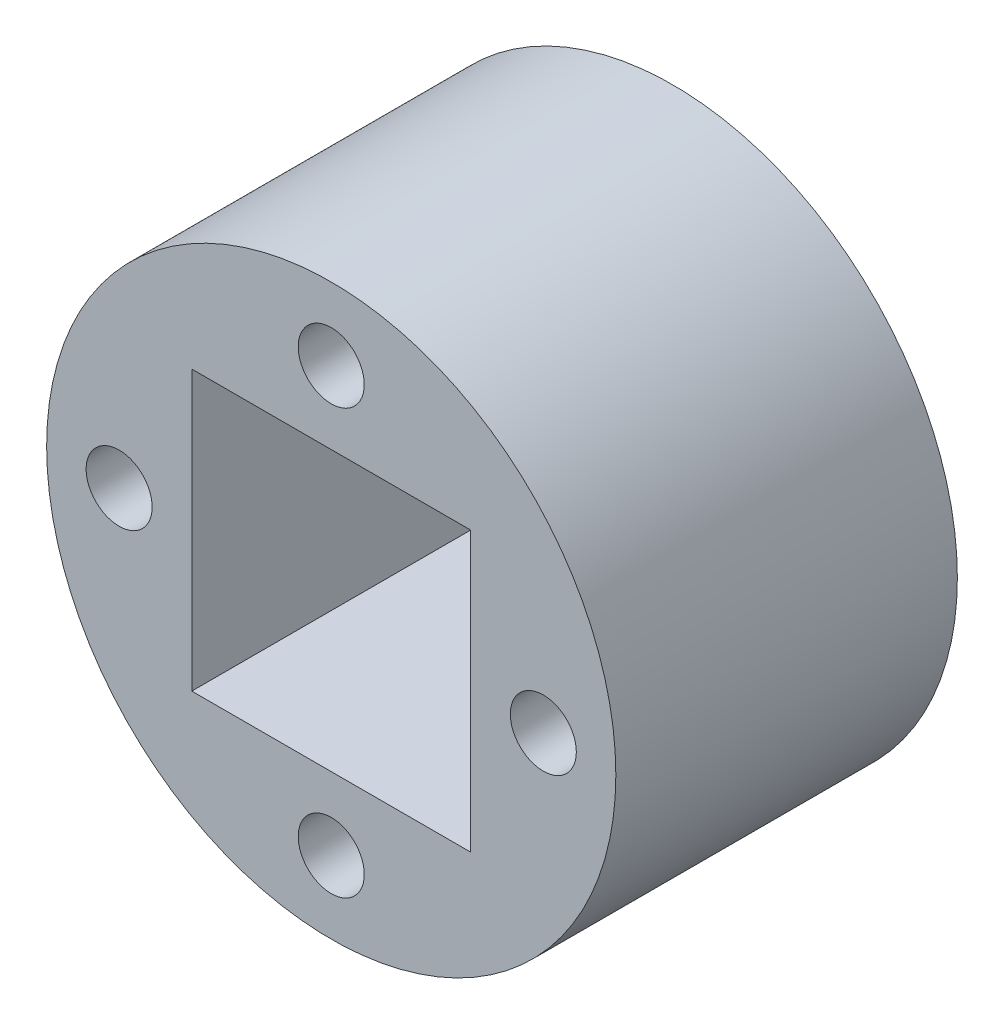
SolidWorks part; units mm, degrees
ref_plane "Front Plane" through (0, 0, 0) normal (0, 0, 1) x (1, 0, 0)
ref_plane "Top Plane" through (0, 0, 0) normal (0, 1, 0) x (1, 0, 0)
ref_plane "Right Plane" through (0, 0, 0) normal (1, 0, 0) x (0, 0, -1)
sketch "Sketch1" plane through (0, 0, 0) normal (0, 0, 1) x (1, 0, 0)
  circle A0 centre (0, 0) radius 12.5
  dimension "D2" = 25
extrude "Boss-Extrude1" add sketch "Sketch1" along normal mid plane 15
sketch "Sketch10" plane through (0, 0, 7.5) normal (0, 0, 1) x (1, 0, 0)
  circle A0 centre (0, 0) radius 12.5
  dimension "D1" = 25
sketch "Sketch8" plane through (0, 0, 7.5) normal (0, 0, 1) x (1, 0, 0)
  line L2 (-6.125, 6.125) -> (6.125, 6.125)
  line L3 (-6.125, 6.125) -> (-6.125, -6.125)
  line L4 (-6.125, -6.125) -> (6.125, -6.125)
  line L5 (6.125, 6.125) -> (6.125, -6.125)
  line L6 (-6.125, 6.125) -> (6.125, -6.125) construction
  line L7 (-6.125, -6.125) -> (6.125, 6.125) construction
  point P5 (0, 0)
  point P14 (0, 0)
  dimension "D1" = 12.25
extrude "Cut-Extrude1" cut sketch "Sketch8" against normal up to next
sketch "Sketch11" plane through (0, 0, 7.5) normal (0, 0, 1) x (1, 0, 0)
  line L0 (6.125, -6.125) -> (6.125, 6.125) construction
  circle A0 centre (9.315, 0) radius 1.45
  circle A1 centre (0, -9.315) radius 1.45
  circle A2 centre (-9.315, 0) radius 1.45
  circle A3 centre (0, 9.315) radius 1.45
  point P13 (0, 0)
  dimension "D1" = 2.9
  dimension "D2" = 3.19
  dimension "D3" = 4
extrude "Cut-Extrude4" cut sketch "Sketch11" against normal up to next
equation "\"drumDiameter\"= 25"
equation "\"D2@Sketch1\"= \"drumDiameter\""
equation "\"drumLength\"= 15"
equation "\"foamThickness\"= 5"
equation "\"drumAbove\"= 0.6"
equation "\"holderThicc\"= 2"
equation "\"D1@Boss-Extrude1\"=\"drumLength\""
equation "\"squareBarLength\"= 12.25"
equation "\"D1@Sketch8\"=\"squareBarLength\""
equation "\"D1@Sketch10\"=\"drumDiameter\""
equation "\"toothlen\"= 2.5"
